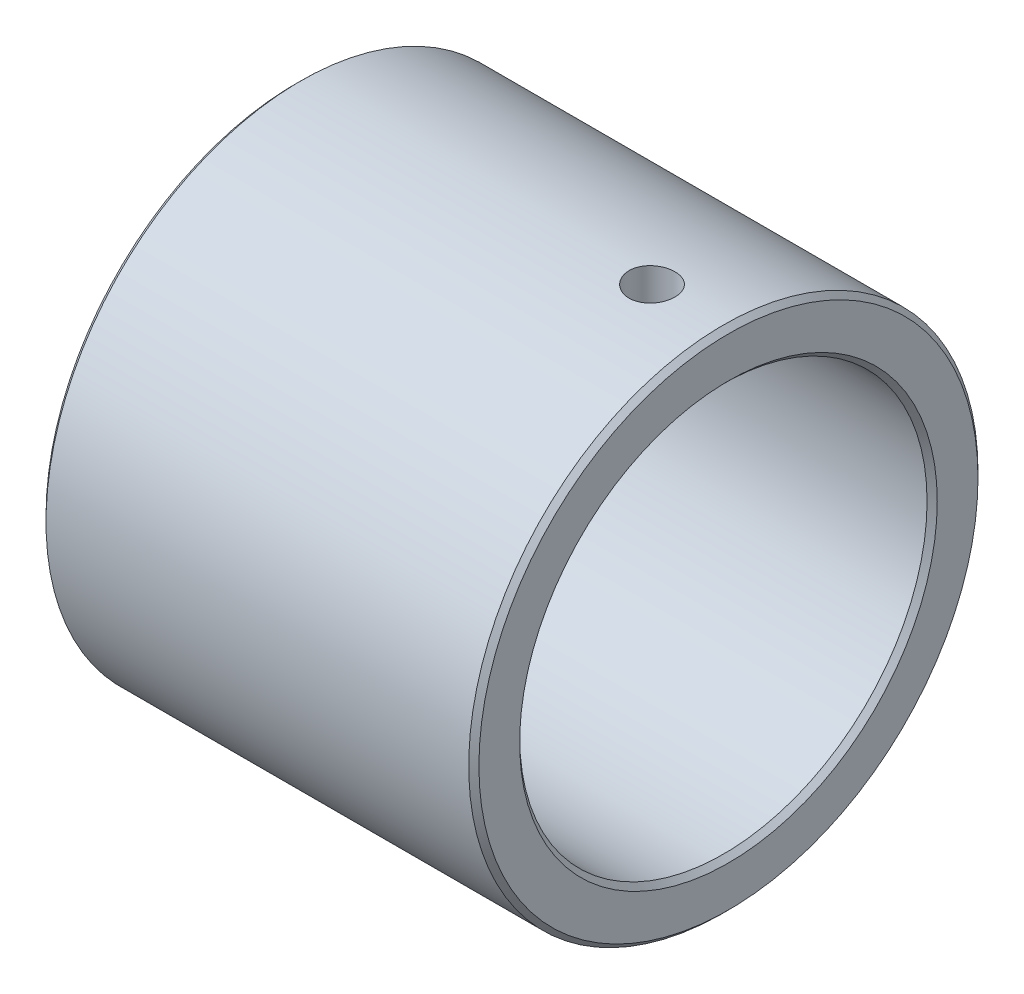
SolidWorks part; units mm, degrees
material "35"
ref_plane "前视基准面" through (0, 0, 0) normal (0, 0, 1) x (1, 0, 0)
ref_plane "上视基准面" through (0, 0, 0) normal (0, 1, 0) x (1, 0, 0)
ref_plane "右视基准面" through (0, 0, 0) normal (1, 0, 0) x (0, 0, -1)
sketch "草图1" plane through (0, 0, 0) normal (1, 0, 0) x (0, 0, -1)
  circle A0 centre (0, 0) radius 50
  circle A1 centre (0, 0) radius 40
  dimension "D1" = 100
  dimension "D2" = 80
extrude "凸台-拉伸1" add sketch "草图1" along normal blind 85
chamfer "倒角1" distance 1 angle 45 4 edges at (85, 0, -40) (85, 0, -50) (0, 0, -40) (0, 0, -50)
ref_plane "基准面1" through (0, 50, 0) normal (0, 1, 0) x (1, 0, 0)
hole_wizard "M10x1.0 螺纹孔1" positions "草图2" profile "草图3" tap size "M10x1.0" standard "GB"
sketch "草图2" plane through (0, 50, 0) normal (0, 1, 0) x (1, 0, 0)
  line L0 (1, -50) -> (84, -50) construction
  line L1 (85, -49) -> (85, 49) construction
  point P0 (70, 0)
  dimension "D1" = 50
  dimension "D2" = 15
sketch "草图3" plane through (70, 50, 0) normal (1, 0, 0) x (0, 0, 1)
  line L0 (0, 0) -> (0, 27.7039)
  line L1 (0, 27.7039) -> (4.5, 25)
  line L2 (4.5, 25) -> (4.5, 0)
  line L5 (4.5, 0) -> (0, 0)
  line L10 (0, 27.7039) -> (-4.5, 25) construction
  line L11 (0, -6.35) -> (0, 107.95) construction
  dimension "螺纹孔钻头直径" = 9
  dimension "螺纹孔钻头深度" = 25
  dimension "导头角度" = 118
cosmetic thread "孔螺蚊线1" parameters "D1"=10.2539, "D2"=10
